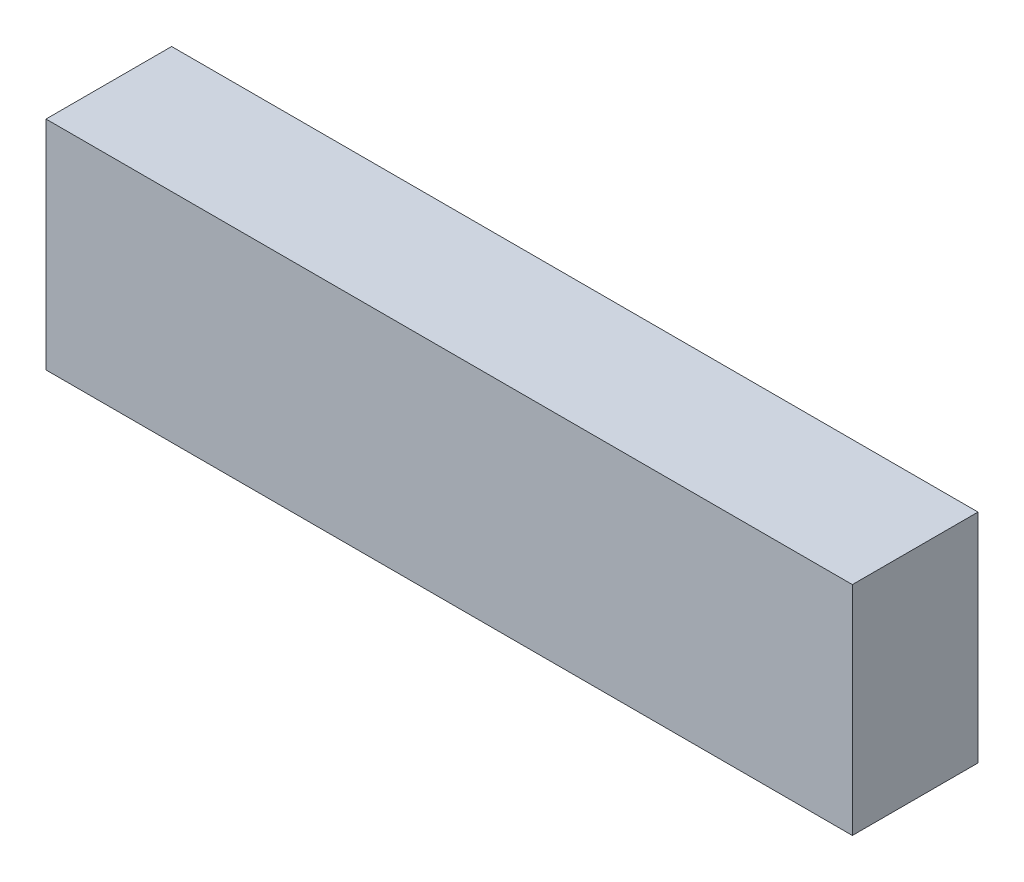
SolidWorks part; units mm, degrees
ref_plane "Front Plane" through (0, 0, 0) normal (0, 0, 1) x (1, 0, 0)
ref_plane "Top Plane" through (0, 0, 0) normal (0, 1, 0) x (1, 0, 0)
ref_plane "Right Plane" through (0, 0, 0) normal (1, 0, 0) x (0, 0, -1)
sketch "Sketch1" plane through (0, 0, 0) normal (0, 0, 1) x (1, 0, 0)
  line L0 (32.3045, -33.37) -> (79.2368, -33.37) construction
  line L1 (32.5045, -33.57) -> (79.0368, -33.57)
  line L2 (32.5045, -33.57) -> (32.5045, -46.11)
  line L3 (32.5045, -46.11) -> (79.0368, -46.11)
  line L4 (79.0368, -33.57) -> (79.0368, -46.11)
  line L5 (79.2368, -46.31) -> (79.2368, -33.37) construction
  line L6 (79.2368, -46.31) -> (32.3045, -46.31) construction
  line L7 (32.3045, -46.31) -> (32.3045, -33.37) construction
  dimension "D1" = 0.2
  dimension "D2" = 0.2
  dimension "D3" = 0.2
  dimension "D4" = 0.2
extrude "Boss-Extrude1" add sketch "Sketch1" along normal blind 7.25
shell "Shell1" thickness 0.5
equation "\"D2@Sketch1\"=\"D1@Sketch1\""
equation "\"D3@Sketch1\"=\"D1@Sketch1\""
equation "\"D4@Sketch1\"=\"D1@Sketch1\""
